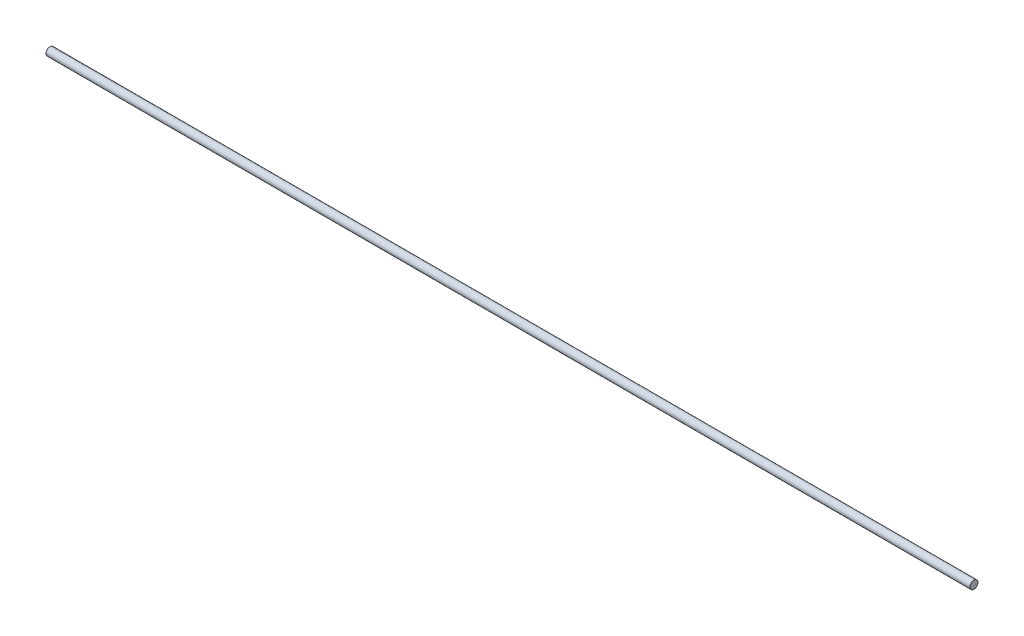
SolidWorks part; units mm, degrees
ref_plane "Front Plane" through (0, 0, 0) normal (0, 0, 1) x (1, 0, 0)
ref_plane "Top Plane" through (0, 0, 0) normal (0, 1, 0) x (1, 0, 0)
ref_plane "Right Plane" through (0, 0, 0) normal (1, 0, 0) x (0, 0, -1)
sketch "Sketch1" plane through (0, 0, 0) normal (1, 0, 0) x (0, 0, -1)
  circle A0 centre (0, 0) radius 3.9688
  dimension "D1" = 7.9375
extrude "Boss-Extrude1" add sketch "Sketch1" along normal blind 914.4
